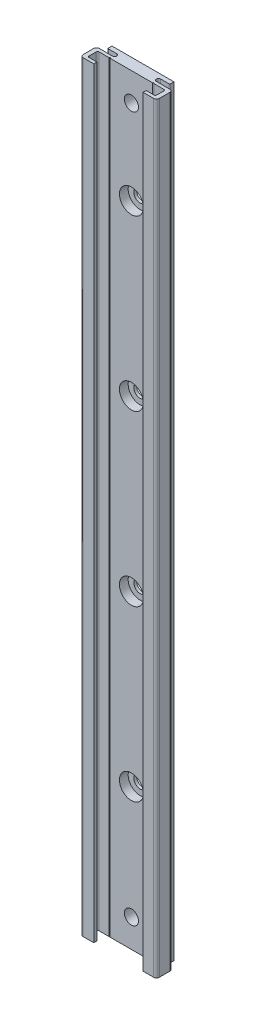
SolidWorks part; units mm, degrees
ref_plane "Front Plane" through (0, 0, 0) normal (0, 0, 1) x (1, 0, 0)
ref_plane "Top Plane" through (0, 0, 0) normal (0, 1, 0) x (1, 0, 0)
ref_plane "Right Plane" through (0, 0, 0) normal (1, 0, 0) x (0, 0, -1)
ref_plane "Plane1" through (0, 300, 0) normal (0, 1, 0) x (1, 0, 0)
sketch "Sketch1" plane through (0, 300, 0) normal (0, 1, 0) x (1, 0, 0)
  line L0 (-13.5, -3) -> (-13.5, -8.7)
  line L1 (-13.5, -8.7) -> (13.5, -8.7)
  line L2 (13.5, -8.7) -> (13.5, -3)
  line L3 (13.5, -3) -> (7.8, -3)
  line L4 (7.8, -1.5) -> (11, -1.5)
  line L5 (11, -1.5) -> (11, 0)
  line L6 (11, 0) -> (-11, 0)
  line L7 (-11, 0) -> (-11, -1.5)
  line L8 (-11, -1.5) -> (-7.8, -1.5)
  line L9 (-7.8, -3) -> (-13.5, -3)
  arc A0 (7.8, -3) -> (7.8, -1.5) centre (7.8, -2.25) cw
  arc A1 (-7.8, -1.5) -> (-7.8, -3) centre (-7.8, -2.25) cw
extrude "Boss-Extrude1" add sketch "Sketch1" against normal blind 270
sketch "Sketch2" plane through (0, 30, 0) normal (0, -1, 0) x (1, 0, 0)
  line L0 (8.75, 8.7) -> (-8.75, 8.7)
  line L1 (-8.75, 8.7) -> (-8.75, 7.6)
  line L2 (-8.75, 7.6) -> (-12, 7.6)
  line L3 (-12, 7.6) -> (-12, 4.1)
  line L4 (-12, 4.1) -> (12, 4.1)
  line L5 (12, 4.1) -> (12, 7.6)
  line L6 (12, 7.6) -> (8.75, 7.6)
  line L7 (8.75, 7.6) -> (8.75, 8.7)
extrude "Cut-Extrude1" cut sketch "Sketch2" against normal through all
hole_wizard "Ø0.4 (0.4) Diameter Hole1" positions "Sketch4" profile "Sketch3" hole size "Ø0.4" standard "ANSI Metric"
sketch "Sketch4" plane through (0, 300, 0) normal (0, 1, 0) x (1, 0, 0)
  point P0 (-7.75, -4.1)
  point P1 (7.75, -4.1)
sketch "Sketch3" plane through (-7.75, 300, 4.1) normal (1, 0, 0) x (0, 0, 1)
  line L0 (0, 0) -> (0, 270)
  line L1 (0, 270) -> (0.2, 270)
  line L2 (0.2, 270) -> (0.2, 0)
  line L5 (0.2, 0) -> (0, 0)
  line L11 (0, -6.35) -> (0, 107.95) construction
  dimension "Thru Hole Dia." = 0.4
  dimension "Thru Hole Depth" = 270
hole_wizard "CBORE for M4 Hex Head Machine Screw1" positions "Sketch6" profile "Sketch5" counterbore size "M4" standard "ANSI Metric"
sketch "Sketch6" plane through (0, 0, 4.1) normal (0, 0, 1) x (1, 0, 0)
  point P0 (0, 260)
  point P1 (0, 200)
  point P2 (0, 140)
  point P3 (0, 80)
  point P4 (0, 20)
sketch "Sketch5" plane through (0, 260, 4.1) normal (1, 0, 0) x (0, -1, 0)
  line L0 (0, 0) -> (0, 4.1)
  line L1 (0, 4.1) -> (2.25, 4.1)
  line L3 (2.25, 4.1) -> (2.25, 3.1)
  line L4 (2.25, 3.1) -> (4.25, 3.1)
  line L5 (4.25, 3.1) -> (4.25, 0)
  line L7 (4.25, 0) -> (0, 0)
  line L11 (0, -6.35) -> (0, 107.95) construction
  dimension "Thru Hole Dia." = 4.5
  dimension "Thru Hole Depth" = 4.1
  dimension "C'Bore Dia." = 8.5
  dimension "C'Bore Depth" = 3.1
fillet "Fillet1" radius 0.2 2 edges at (11, 165, 1.5) (-11, 165, 1.5)
fillet "Fillet2" radius 0.5 4 edges at (12, 165, 4.1) (-12, 165, 7.6) (12, 165, 7.6) (-12, 165, 4.1)
fillet "Fillet3" radius 1 4 edges at (-13.5, 165, 8.7) (-13.5, 165, 3) (13.5, 165, 3) (13.5, 165, 8.7)
sketch "Sketch7" plane through (0, 0, 4.1) normal (0, 0, 1) x (1, 0, 0)
  line L0 (0, 300) -> (0, 30) construction
  line L1 (-7.55, 300) -> (7.55, 300) construction
  line L2 (-7.55, 30) -> (7.55, 30) construction
  circle A0 centre (0, 290) radius 2.5
  circle A1 centre (0, 40) radius 2.5
  dimension "D2" = 5
  dimension "D4" = 5
  dimension "D5" = 10
  dimension "D7" = 10
extrude "Cut-Extrude2" cut sketch "Sketch7" against normal up to next
